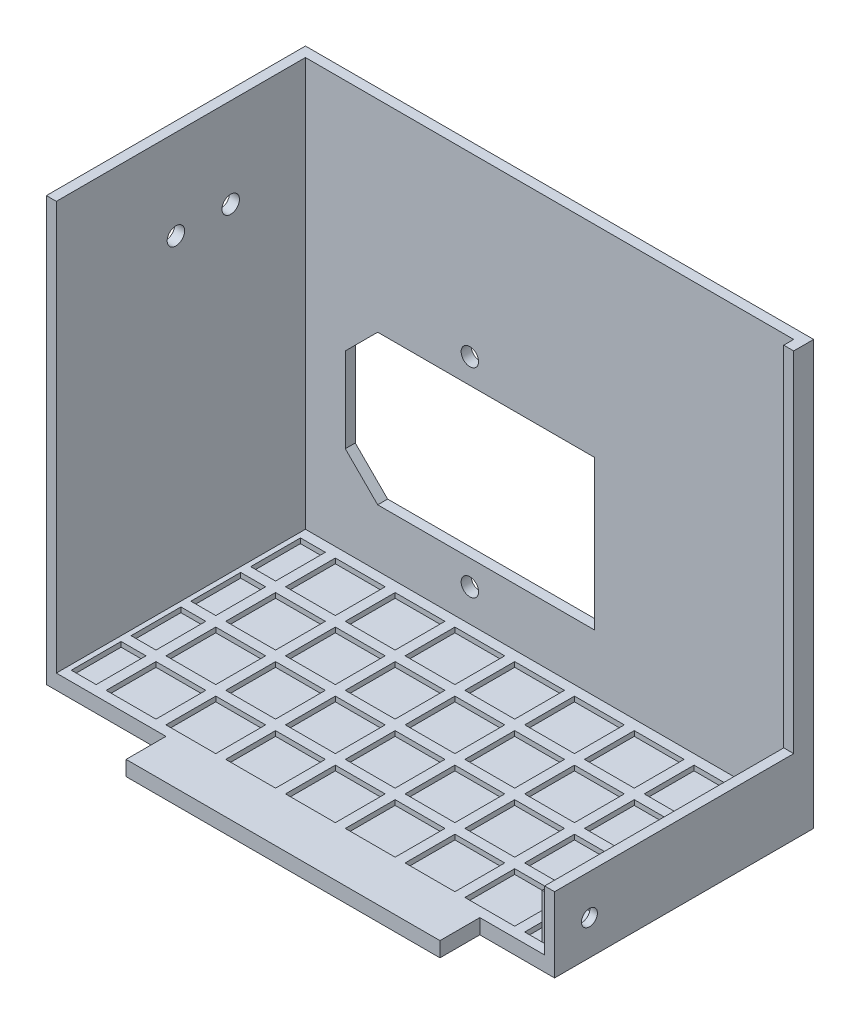
SolidWorks part; units mm, degrees
ref_plane "Front Plane" through (0, 0, 0) normal (0, 0, 1) x (1, 0, 0)
ref_plane "Top Plane" through (0, 0, 0) normal (0, 1, 0) x (1, 0, 0)
ref_plane "Right Plane" through (0, 0, 0) normal (1, 0, 0) x (0, 0, -1)
sketch "Sketch1" plane through (0, 0, 0) normal (0, 1, 0) x (1, 0, 0)
  line L1 (0, 0) -> (102, 0)
  line L2 (0, 0) -> (0, 52)
  line L3 (0, 52) -> (102, 52)
  line L4 (102, 0) -> (102, 52)
  line L5 (24, 0) -> (87, 0)
  line L6 (24, 0) -> (24, -8)
  line L7 (24, -8) -> (87, -8)
  line L8 (87, 0) -> (87, -8)
  dimension "D1" = 52
  dimension "D2" = 102
  dimension "D3" = 15
  dimension "D4" = 63
  dimension "D5" = 8
extrude "Boss-Extrude1" add sketch "Sketch1" along normal blind 3 contours L1 L4 L3 L2 | L8 L1 L6 L7
sketch "Sketch2" plane through (0, 3, 0) normal (0, 1, 0) x (1, 0, 0)
  line L0 (0, 0) -> (0, 52)
  line L1 (0, 52) -> (102, 52)
  line L2 (102, 52) -> (102, 48)
  line L3 (102, 0) -> (102, 52) construction
  line L4 (2, 0) -> (2, 50)
  line L5 (2, 50) -> (100, 50)
  line L6 (100, 50) -> (100, 48)
  line L7 (2, 0) -> (0, 0)
  line L8 (100, 48) -> (102, 48)
  dimension "D1" = 4
  dimension "D2" = 2
extrude "Boss-Extrude2" add sketch "Sketch2" along normal blind 82
sketch "Sketch3" plane through (0, 3, 0) normal (0, 1, 0) x (1, 0, 0)
  line L0 (87, 0) -> (102, 0) construction
  line L1 (102, 48) -> (100, 48)
  line L2 (102, 48) -> (102, 0)
  line L3 (102, 0) -> (100, 0)
  line L4 (100, 48) -> (100, 0)
  dimension "D1" = 2
extrude "Boss-Extrude3" add sketch "Sketch3" along normal blind 12
sketch "Sketch4" plane through (102, 0, 0) normal (1, 0, 0) x (0, 0, -1)
  line L0 (0, 3) -> (7, 3) construction
  line L1 (7, 3) -> (7, 7) construction
  circle A0 centre (7, 7) radius 1.6
  dimension "D3" = 3.2
  dimension "D1" = 7
  dimension "D2" = 4
extrude "Cut-Extrude1" cut sketch "Sketch4" against normal up to next
sketch "Sketch5" plane through (0, 3, 0) normal (0, 1, 0) x (1, 0, 0)
  line L0 (102, 0) -> (102, 48) construction
  line L1 (92, 2) -> (82, 2)
  line L2 (92, 2) -> (92, 12)
  line L3 (92, 12) -> (82, 12)
  line L4 (82, 2) -> (82, 12)
  line L5 (87, 0) -> (100, 0) construction
  line L6 (80, 12) -> (70, 12)
  line L7 (70, 2) -> (70, 12)
  line L8 (80, 2) -> (70, 2)
  line L9 (80, 2) -> (80, 12)
  line L10 (68, 12) -> (58, 12)
  line L11 (58, 2) -> (58, 12)
  line L12 (68, 2) -> (58, 2)
  line L13 (68, 2) -> (68, 12)
  line L14 (56, 12) -> (46, 12)
  line L15 (46, 2) -> (46, 12)
  line L16 (56, 2) -> (46, 2)
  line L17 (56, 2) -> (56, 12)
  line L18 (44, 12) -> (34, 12)
  line L19 (34, 2) -> (34, 12)
  line L20 (44, 2) -> (34, 2)
  line L21 (44, 2) -> (44, 12)
  line L22 (32, 12) -> (22, 12)
  line L23 (22, 2) -> (22, 12)
  line L24 (32, 2) -> (22, 2)
  line L25 (32, 2) -> (32, 12)
  line L26 (20, 12) -> (10, 12)
  line L27 (10, 2) -> (10, 12)
  line L28 (20, 2) -> (10, 2)
  line L29 (20, 2) -> (20, 12)
  line L30 (80, 24) -> (70, 24)
  line L31 (70, 14) -> (70, 24)
  line L32 (80, 14) -> (70, 14)
  line L33 (80, 14) -> (80, 24)
  line L34 (68, 24) -> (58, 24)
  line L35 (58, 14) -> (58, 24)
  line L36 (68, 14) -> (58, 14)
  line L37 (68, 14) -> (68, 24)
  line L38 (56, 24) -> (46, 24)
  line L39 (46, 14) -> (46, 24)
  line L40 (56, 14) -> (46, 14)
  line L41 (56, 14) -> (56, 24)
  line L42 (44, 24) -> (34, 24)
  line L43 (34, 14) -> (34, 24)
  line L44 (44, 14) -> (34, 14)
  line L45 (44, 14) -> (44, 24)
  line L46 (32, 24) -> (22, 24)
  line L47 (22, 14) -> (22, 24)
  line L48 (32, 14) -> (22, 14)
  line L49 (32, 14) -> (32, 24)
  line L50 (20, 24) -> (10, 24)
  line L51 (10, 14) -> (10, 24)
  line L52 (20, 14) -> (10, 14)
  line L53 (20, 14) -> (20, 24)
  line L54 (80, 36) -> (70, 36)
  line L55 (70, 26) -> (70, 36)
  line L56 (80, 26) -> (70, 26)
  line L57 (80, 26) -> (80, 36)
  line L58 (68, 36) -> (58, 36)
  line L59 (58, 26) -> (58, 36)
  line L60 (68, 26) -> (58, 26)
  line L61 (68, 26) -> (68, 36)
  line L62 (56, 36) -> (46, 36)
  line L63 (46, 26) -> (46, 36)
  line L64 (56, 26) -> (46, 26)
  line L65 (56, 26) -> (56, 36)
  line L66 (44, 36) -> (34, 36)
  line L67 (34, 26) -> (34, 36)
  line L68 (44, 26) -> (34, 26)
  line L69 (44, 26) -> (44, 36)
  line L70 (32, 36) -> (22, 36)
  line L71 (22, 26) -> (22, 36)
  line L72 (32, 26) -> (22, 26)
  line L73 (32, 26) -> (32, 36)
  line L74 (20, 36) -> (10, 36)
  line L75 (10, 26) -> (10, 36)
  line L76 (20, 26) -> (10, 26)
  line L77 (20, 26) -> (20, 36)
  line L78 (80, 48) -> (70, 48)
  line L79 (70, 38) -> (70, 48)
  line L80 (80, 38) -> (70, 38)
  line L81 (80, 38) -> (80, 48)
  line L82 (68, 48) -> (58, 48)
  line L83 (58, 38) -> (58, 48)
  line L84 (68, 38) -> (58, 38)
  line L85 (68, 38) -> (68, 48)
  line L86 (56, 48) -> (46, 48)
  line L87 (46, 38) -> (46, 48)
  line L88 (56, 38) -> (46, 38)
  line L89 (56, 38) -> (56, 48)
  line L90 (44, 48) -> (34, 48)
  line L91 (34, 38) -> (34, 48)
  line L92 (44, 38) -> (34, 38)
  line L93 (44, 38) -> (44, 48)
  line L94 (32, 48) -> (22, 48)
  line L95 (22, 38) -> (22, 48)
  line L96 (32, 38) -> (22, 38)
  line L97 (32, 38) -> (32, 48)
  line L98 (20, 48) -> (10, 48)
  line L99 (10, 38) -> (10, 48)
  line L100 (20, 38) -> (10, 38)
  line L101 (20, 38) -> (20, 48)
  line L102 (92, 24) -> (82, 24)
  line L103 (82, 14) -> (82, 24)
  line L104 (92, 14) -> (82, 14)
  line L105 (92, 14) -> (92, 24)
  line L106 (92, 36) -> (82, 36)
  line L107 (82, 26) -> (82, 36)
  line L108 (92, 26) -> (82, 26)
  line L109 (92, 26) -> (92, 36)
  line L110 (92, 48) -> (82, 48)
  line L111 (82, 38) -> (82, 48)
  line L112 (92, 38) -> (82, 38)
  line L113 (92, 38) -> (92, 48)
  line L114 (2, 0) -> (24, 0) construction
  line L115 (8, 2) -> (3, 2)
  line L116 (8, 2) -> (8, 12)
  line L117 (8, 12) -> (3, 12)
  line L118 (3, 2) -> (3, 12)
  line L119 (8, 24) -> (3, 24)
  line L120 (3, 14) -> (3, 24)
  line L121 (8, 14) -> (3, 14)
  line L122 (8, 14) -> (8, 24)
  line L123 (8, 36) -> (3, 36)
  line L124 (3, 26) -> (3, 36)
  line L125 (8, 26) -> (3, 26)
  line L126 (8, 26) -> (8, 36)
  line L127 (8, 48) -> (3, 48)
  line L128 (3, 38) -> (3, 48)
  line L129 (8, 38) -> (3, 38)
  line L130 (8, 38) -> (8, 48)
  line L132 (102, 52) -> (0, 52) construction
  line L133 (94, 48) -> (98, 48)
  line L134 (94, 48) -> (94, 38)
  line L135 (94, 38) -> (98, 38)
  line L136 (98, 48) -> (98, 38)
  line L137 (94, 36) -> (98, 36)
  line L138 (94, 36) -> (94, 26)
  line L139 (98, 36) -> (98, 26)
  line L140 (94, 26) -> (98, 26)
  line L141 (94, 24) -> (98, 24)
  line L142 (94, 24) -> (94, 14)
  line L143 (98, 24) -> (98, 14)
  line L144 (94, 14) -> (98, 14)
  line L145 (94, 12) -> (98, 12)
  line L146 (94, 12) -> (94, 2)
  line L147 (98, 12) -> (98, 2)
  line L148 (94, 2) -> (98, 2)
  dimension "D1" = 10
  dimension "D2" = 10
  dimension "D3" = 10
  dimension "D4" = 2
  dimension "D7" = 2
  dimension "D8" = 2
  dimension "D9" = 10
  dimension "D10" = 2
  dimension "D11" = 2
  dimension "D12" = 5
  dimension "D13" = 10
  dimension "D15" = 2
  dimension "D16" = 4
  dimension "D17" = 2
  dimension "D18" = 10
  dimension "D19" = 4
  dimension "D21" = 2
  dimension "D5" = 7
  dimension "D6" = 4
  dimension "D14" = 4
  dimension "D20" = 4
extrude "Cut-Extrude2" cut sketch "Sketch5" against normal blind 1
sketch "Sketch6" plane through (102, 0, 0) normal (1, 0, 0) x (0, 0, -1)
  line L1 (2, 2) -> (12, 2)
  line L2 (2, 2) -> (2, 12)
  line L3 (2, 12) -> (12, 12)
  line L4 (12, 2) -> (12, 12)
  line L5 (2, 2) -> (12, 12) construction
  line L6 (2, 12) -> (12, 2) construction
  circle A0 centre (7, 7) radius 1.6
  point P0 (7, 7)
  dimension "D3" = 3.2
  dimension "D1" = 10
  dimension "D2" = 10
extrude "Boss-Extrude4" add sketch "Sketch6" against normal blind 4.5
sketch "Sketch7" plane through (97.5, 0, 0) normal (-1, 0, 0) x (0, 0, 1)
  line L0 (-7, 7) -> (-4, 7) construction
  line L1 (-4.2504, 8.5875) -> (-7, 7) construction
  line L2 (-4.2504, 8.5875) -> (-7, 10.175)
  line L3 (-7, 10.175) -> (-9.7496, 8.5875)
  line L4 (-9.7496, 8.5875) -> (-9.7496, 5.4125)
  line L5 (-9.7496, 5.4125) -> (-7, 3.825)
  line L6 (-7, 3.825) -> (-4.2504, 5.4125)
  line L7 (-4.2504, 5.4125) -> (-4.2504, 8.5875)
  circle A0 centre (-7, 7) radius 3.175 construction
  dimension "D2" = 6.35
  dimension "D1" = 3
  dimension "D3" = 30
extrude "Cut-Extrude3" cut sketch "Sketch7" against normal blind 3
sketch "Sketch8" plane through (0, 0, -52) normal (0, 0, -1) x (-1, 0, 0)
  line L0 (-35, 49.5) -> (-35, 9.5) construction
  line L1 (-16.5, 14.5) -> (-60, 14.5)
  line L2 (-10, 21) -> (-10, 38)
  line L3 (-16.5, 44.5) -> (-60, 44.5)
  line L4 (-60, 14.5) -> (-60, 44.5)
  line L5 (0, 85) -> (0, 0) construction
  line L6 (0, 0) -> (-102, 0) construction
  line L7 (-10, 38) -> (-16.5, 44.5)
  line L8 (-16.5, 14.5) -> (-10, 21)
  circle A0 centre (-35, 49.5) radius 1.75
  circle A1 centre (-35, 9.5) radius 1.75
  point P0 (-10, 14.5)
  point P2 (-10, 44.5)
  dimension "D6" = 3.5
  dimension "D7" = 3.5
  dimension "D8" = 35
  dimension "D9" = 9.5
  dimension "D1" = 30
  dimension "D2" = 50
  dimension "D3" = 40
  dimension "D4" = 5
  dimension "D5" = 25
extrude "Cut-Extrude4" cut sketch "Sketch8" against normal blind 3
sketch "Sketch9" plane through (0, 0, 0) normal (-1, 0, 0) x (0, 0, 1)
  line L0 (-24, 67) -> (-35, 67) construction
  line L1 (0, 85) -> (0, 0) construction
  line L2 (-52, 85) -> (0, 85) construction
  circle A0 centre (-24, 67) radius 1.75
  circle A1 centre (-35, 67) radius 1.75
  dimension "D4" = 3.5
  dimension "D5" = 3.5
  dimension "D1" = 11
  dimension "D2" = 24
  dimension "D3" = 18
extrude "Cut-Extrude5" cut sketch "Sketch9" against normal blind 3
